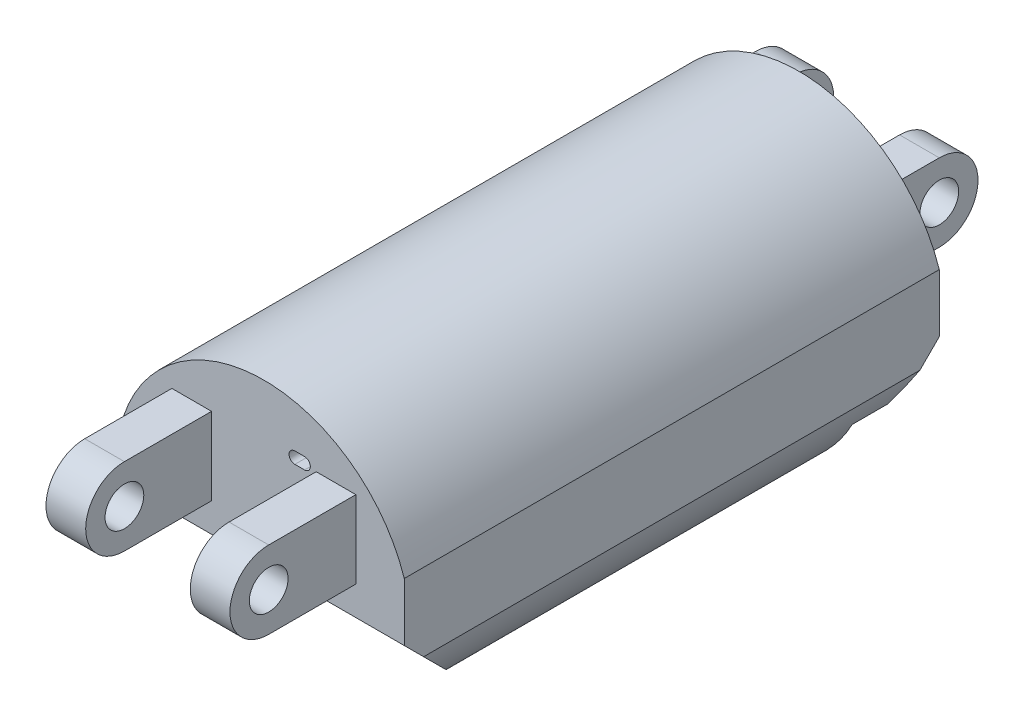
SolidWorks part; units mm, degrees
material "PET"
ref_plane "Front Plane" through (0, 0, 0) normal (0, 0, 1) x (1, 0, 0)
ref_plane "Top Plane" through (0, 0, 0) normal (0, 1, 0) x (1, 0, 0)
ref_plane "Right Plane" through (0, 0, 0) normal (1, 0, 0) x (0, 0, -1)
sketch "Sketch1" plane through (0, 0, 0) normal (0, 0, 1) x (1, 0, 0)
  line L0 (0, 0) -> (0, 5.08)
  line L3 (18.415, 5.08) -> (18.415, 0)
  arc A2 (0, 5.08) -> (18.415, 5.08) centre (9.2075, 2.0562) cw
  arc A3 (0, 0) -> (18.415, 0) centre (9.2075, 3.0238) ccw
  point P2 (9.2075, -6.6675)
  point P8 (9.2075, 11.7475)
  dimension "D1" = 18.415
  dimension "D2" = 18.415
  dimension "D3" = 5.08
extrude "Boss-Extrude1" add sketch "Sketch1" along normal mid plane 35.0838 contours A2 L3 A3 L0
sketch "Sketch2" plane through (0, 0, 0) normal (1, 0, 0) x (0, 0, -1)
  line L4 (15.875, 2.54) -> (-49984.125, 2.54) construction
  line L5 (17.5419, 5.08) -> (17.5419, 0) construction
  line L6 (-17.5419, 5.08) -> (-17.5419, 0) construction
  line L10 (0, -1000) -> (0, 49000) construction
  line L18 (-17.5419, 1.27) -> (-17.5419, -6.6675)
  line L23 (17.5419, -6.6675) -> (9.6044, -6.6675)
  line L24 (17.5419, 1.27) -> (17.5419, -6.6675)
  line L32 (-17.5419, -6.6675) -> (-9.6044, -6.6675)
  line L33 (-17.5419, -6.6675) -> (17.5419, -6.6675) construction
  line L34 (-9.6044, -6.6675) -> (-17.5419, 1.27)
  line L35 (9.6044, -6.6675) -> (17.5419, 1.27)
  line L36 (-17.5419, -6.6675) -> (17.5419, -6.6675) construction
  point P0 (-15.0884, 2.54)
  point P11 (17.5419, 2.54)
  point P14 (-17.5419, 2.54)
  dimension "D2" = 1.27
  dimension "D4" = 45
extrude "Cut-Extrude1" cut sketch "Sketch2" along normal through all
sketch "Sketch3" plane through (0, 0, 17.5419) normal (0, 0, 1) x (1, 0, 0)
  line L0 (21.7393, 2.54) -> (-3.7187, 2.54) construction
  line L2 (9.2075, 13.3103) -> (9.2075, -9.2077) construction
  arc A0 (18.415, 5.08) -> (0, 5.08) centre (9.2075, 2.0562) ccw construction
  arc A3 (18.415, 5.08) -> (0, 5.08) centre (9.2075, 2.0562) ccw
  arc A5 (17.2084, 4.6837) -> (1.2066, 4.6837) centre (9.2075, 2.0562) ccw
  arc A6 (6.0894, 9.879) -> (12.3256, 9.879) centre (9.2075, 10.4775) ccw
  arc A7 (17.2084, 0.3963) -> (1.2066, 0.3963) centre (9.2075, 3.0238) cw
  arc A8 (6.0894, -4.799) -> (12.3256, -4.799) centre (9.2075, -5.3975) cw
  point P9 (9.2075, 11.7475)
  point P14 (9.2075, 7.3025)
  dimension "D1" = 2.54
  dimension "D2" = 1.27
  dimension "D4" = 3.175
extrude "Cut-Extrude2" cut sketch "Sketch3" against normal through all both and the other way through all contours A8 A7
ref_plane "Plane1" through (14.605, 0, 0) normal (1, 0, 0) x (0, 0, -1)
sketch "Sketch4" plane through (14.605, 0, 0) normal (1, 0, 0) x (0, 0, -1)
  line L0 (-17.5419, 8.255) -> (-20.7169, 8.255)
  line L1 (-17.5419, 8.255) -> (-17.5419, 3.175)
  line L2 (-17.5419, 3.175) -> (-20.7169, 3.175)
  line L3 (-17.5419, 5.08) -> (-17.5419, 1.27) construction
  line L4 (-16.2719, 0) -> (16.2719, 0) construction
  arc A0 (-20.7169, 8.255) -> (-20.7169, 3.175) centre (-20.7169, 5.715) ccw
  circle A1 centre (-20.7169, 5.715) radius 1.27
  dimension "D2" = 2.54
  dimension "D1" = 5.08
  dimension "D3" = 3.175
  dimension "D4" = 3.175
extrude "Boss-Extrude2" add sketch "Sketch4" along normal mid plane 1.27
sketch "Sketch5" plane through (13.97, 0, 0) normal (-1, 0, 0) x (0, 0, 1)
  line L3 (17.5419, 8.255) -> (17.5419, 3.175)
  line L4 (17.5419, 3.175) -> (20.7169, 3.175)
  line L5 (20.7169, 8.255) -> (17.5419, 8.255)
  line L6 (17.5419, 8.255) -> (17.5419, 3.175)
  line L7 (17.5419, 3.175) -> (20.7169, 3.175)
  line L8 (20.7169, 8.255) -> (17.5419, 8.255)
  circle A0 centre (20.7169, 5.715) radius 1.27 construction
  arc A1 (20.7169, 3.175) -> (20.7169, 8.255) centre (20.7169, 5.715) ccw
  arc A2 (20.7169, 3.175) -> (20.7169, 8.255) centre (20.7169, 5.715) ccw
  circle A3 centre (20.7169, 5.715) radius 1.27
  dimension "D1" = 0
extrude "Boss-Extrude3" add sketch "Sketch5" along normal blind 1.3323
ref_plane "Plane2" through (9.2075, 0, 0) normal (1, 0, 0) x (0, 0, -1)
mirror "Mirror1" about plane through (9.2075, 0, 0) normal (1, 0, 0) of "Boss-Extrude3", "Boss-Extrude2"
mirror "Mirror2" about plane through (0, 0, 0) normal (0, 0, 1) of "Mirror1", "Boss-Extrude3", "Boss-Extrude2"
sketch "Sketch8" [suppressed] plane through (15.24, 0, 0) normal (1, 0, 0) x (0, 0, -1)
  line L3 (17.5419, 8.255) -> (17.5419, 3.175)
  line L4 (17.5419, 3.175) -> (20.7169, 3.175)
  line L5 (20.7169, 8.255) -> (17.5419, 8.255)
  line L6 (17.5419, 8.255) -> (17.5419, 3.175)
  line L7 (17.5419, 3.175) -> (20.7169, 3.175)
  line L8 (20.7169, 8.255) -> (17.5419, 8.255)
  circle A0 centre (20.7169, 5.715) radius 1.27 construction
  arc A1 (20.7169, 3.175) -> (20.7169, 8.255) centre (20.7169, 5.715) ccw
  arc A2 (20.7169, 3.175) -> (20.7169, 8.255) centre (20.7169, 5.715) ccw
  circle A3 centre (20.7169, 5.715) radius 1.27
  dimension "D1" = 0
extrude "Cut-Extrude4" [suppressed] cut sketch "Sketch8" against normal blind 1.27
sketch "Sketch9" [suppressed] plane through (12.6377, 0, 0) normal (-1, 0, 0) x (0, 0, 1)
  line L3 (-17.5419, 8.255) -> (-20.7169, 8.255)
  line L4 (-20.7169, 3.175) -> (-17.5419, 3.175)
  line L5 (-17.5419, 3.175) -> (-17.5419, 8.255)
  line L6 (-17.5419, 8.255) -> (-20.7169, 8.255)
  line L7 (-20.7169, 3.175) -> (-17.5419, 3.175)
  line L8 (-17.5419, 3.175) -> (-17.5419, 8.255)
  circle A1 centre (-20.7169, 5.715) radius 1.27
  circle A2 centre (-20.7169, 5.715) radius 1.27
  arc A3 (-20.7169, 8.255) -> (-20.7169, 3.175) centre (-20.7169, 5.715) ccw
  arc A4 (-20.7169, 8.255) -> (-20.7169, 3.175) centre (-20.7169, 5.715) ccw
  dimension "D1" = 0
  dimension "D2" = 0
extrude "Boss-Extrude5" [suppressed] add sketch "Sketch9" along normal blind 0.635
mirror "Mirror5" [suppressed] about plane through (9.2075, 0, 0) normal (1, 0, 0)
sketch "Sketch10" plane through (15.24, 0, 0) normal (1, 0, 0) x (0, 0, -1)
  line L0 (-20.7169, 3.175) -> (-17.5419, 3.175) construction
  line L1 (-17.5419, 8.255) -> (-23.2569, 8.255)
  line L2 (-17.5419, 8.255) -> (-17.5419, 3.175)
  line L3 (-17.5419, 3.175) -> (-23.2569, 3.175)
  arc A1 (-23.2569, 8.255) -> (-23.2569, 3.175) centre (-23.2569, 5.715) ccw
  circle A2 centre (-23.2569, 5.715) radius 1.27
  arc A3 (-20.7169, 8.255) -> (-20.7169, 3.175) centre (-20.7169, 5.715) ccw construction
  dimension "D1" = 2.54
extrude "Boss-Extrude6" add sketch "Sketch10" against normal up to surface (2.6023 mm away) up to face at (12.6377, 5.715, 19.7644)
sketch "Sketch12" plane through (3.175, 0, 0) normal (-1, 0, 0) x (0, 0, 1)
  line L0 (20.7169, 3.175) -> (17.5419, 3.175) construction
  line L1 (17.5419, 8.255) -> (23.2569, 8.255)
  line L2 (17.5419, 8.255) -> (17.5419, 3.175)
  line L3 (17.5419, 3.175) -> (23.2569, 3.175)
  arc A0 (23.2569, 8.255) -> (23.2569, 3.175) centre (23.2569, 5.715) cw
  arc A1 (23.2569, 3.175) -> (23.2569, 8.255) centre (23.2569, 5.715) ccw construction
extrude "Boss-Extrude7" add sketch "Sketch12" against normal up to surface (2.6023 mm away) up to face at (5.7773, 5.715, 21.9869)
sketch "Sketch11" plane through (15.24, 0, 0) normal (1, 0, 0) x (0, 0, -1)
  circle A0 centre (-23.2569, 5.715) radius 1.27
  arc A1 (-22.9394, 6.9447) -> (-22.9394, 4.4853) centre (-20.7169, 5.715) ccw construction
extrude "Cut-Extrude5" cut sketch "Sketch11" against normal up to surface (12.065 mm away) up to face at (3.175, 5.715, 21.0344)
sketch "Sketch16" [suppressed] plane through (12.6377, 0, 0) normal (-1, 0, 0) x (0, 0, 1)
  line L3 (23.2569, 8.255) -> (17.5419, 8.255)
  line L4 (17.5419, 8.255) -> (17.5419, 3.175)
  line L5 (17.5419, 3.175) -> (23.2569, 3.175)
  line L6 (23.2569, 8.255) -> (17.5419, 8.255)
  line L7 (17.5419, 8.255) -> (17.5419, 3.175)
  line L8 (17.5419, 3.175) -> (23.2569, 3.175)
  circle A0 centre (23.2569, 5.715) radius 1.27 construction
  arc A1 (23.2569, 3.175) -> (23.2569, 8.255) centre (23.2569, 5.715) ccw
  arc A2 (23.2569, 3.175) -> (23.2569, 8.255) centre (23.2569, 5.715) ccw
  circle A3 centre (23.2569, 5.715) radius 1.27
  dimension "D1" = 0
extrude "Cut-Extrude7" [suppressed] cut sketch "Sketch16" against normal blind 1.27
sketch "Sketch17" [suppressed] plane through (15.24, 0, 0) normal (1, 0, 0) x (0, 0, -1)
  line L3 (-17.5419, 8.255) -> (-23.2569, 8.255)
  line L4 (-23.2569, 3.175) -> (-17.5419, 3.175)
  line L5 (-17.5419, 3.175) -> (-17.5419, 8.255)
  line L6 (-17.5419, 8.255) -> (-23.2569, 8.255)
  line L7 (-23.2569, 3.175) -> (-17.5419, 3.175)
  line L8 (-17.5419, 3.175) -> (-17.5419, 8.255)
  circle A0 centre (-23.2569, 5.715) radius 1.27 construction
  arc A1 (-23.2569, 8.255) -> (-23.2569, 3.175) centre (-23.2569, 5.715) ccw
  arc A2 (-23.2569, 8.255) -> (-23.2569, 3.175) centre (-23.2569, 5.715) ccw
  circle A3 centre (-23.2569, 5.715) radius 1.27
  dimension "D1" = 0
extrude "Boss-Extrude10" [suppressed] add sketch "Sketch17" against normal blind 2.54
sketch "Sketch19" [suppressed] plane through (13.97, 0, 0) normal (1, 0, 0) x (0, 0, -1)
  line L3 (20.7169, 8.255) -> (17.5419, 8.255)
  line L4 (17.5419, 8.255) -> (17.5419, 3.175)
  line L5 (17.5419, 3.175) -> (20.7169, 3.175)
  line L6 (20.7169, 8.255) -> (17.5419, 8.255)
  line L7 (17.5419, 8.255) -> (17.5419, 3.175)
  line L8 (17.5419, 3.175) -> (20.7169, 3.175)
  circle A0 centre (20.7169, 5.715) radius 1.27 construction
  arc A1 (20.7169, 3.175) -> (20.7169, 8.255) centre (20.7169, 5.715) ccw
  arc A2 (20.7169, 3.175) -> (20.7169, 8.255) centre (20.7169, 5.715) ccw
  circle A3 centre (20.7169, 5.715) radius 1.27
  dimension "D1" = 0
extrude "Boss-Extrude11" [suppressed] add sketch "Sketch19" along normal blind 1.143
mirror "Mirror6" [suppressed] about plane through (9.2075, 0, 0) normal (1, 0, 0)
sketch "Sketch20" plane through (0, 0, -17.5419) normal (0, 0, -1) x (-1, 0, 0)
  line L0 (-21.8226, 5.715) -> (5.8887, 5.715) construction
  line L1 (-18.415, 1.27) -> (-18.415, 0) construction
  line L2 (-17.78, 5.715) -> (-15.24, 5.715)
  line L3 (-17.78, 5.715) -> (-17.78, -6.985)
  line L4 (-17.78, -6.985) -> (-15.24, -6.985)
  line L5 (-15.24, 5.715) -> (-15.24, -6.985)
  line L6 (-3.175, 5.715) -> (-0.635, 5.715)
  line L7 (-3.175, 5.715) -> (-3.175, -6.985)
  line L8 (-3.175, -6.985) -> (-0.635, -6.985)
  line L9 (-0.635, 5.715) -> (-0.635, -6.985)
  dimension "D1" = 2.54
  dimension "D2" = 2.54
  dimension "D3" = 0.635
  dimension "D4" = 0.635
  dimension "D5" = 12.7
  dimension "D6" = 12.7
  dimension "D7" = 5.715
extrude "Cut-Extrude9" cut sketch "Sketch20" against normal blind 5.08
sketch "Sketch21" plane through (0, 0, -17.5419) normal (0, 0, -1) x (-1, 0, 0)
  line L0 (-7.1755, 8.1788) -> (-6.5405, 8.1788) construction
  line L1 (-6.5405, 2.8702) -> (-11.8745, 2.8702)
  line L2 (-6.5405, 2.8702) -> (-6.5405, 8.5598)
  line L3 (-6.5405, 8.5598) -> (-11.8745, 8.5598)
  line L4 (-11.8745, 2.8702) -> (-11.8745, 8.5598)
  line L5 (-6.5405, 2.8702) -> (-11.8745, 8.5598) construction
  line L6 (-6.5405, 8.5598) -> (-11.8745, 2.8702) construction
  line L7 (-7.1755, 8.5598) -> (-6.5405, 8.5598)
  line L8 (-7.1755, 7.7978) -> (-6.5405, 7.7978)
  arc A0 (-7.1755, 8.5598) -> (-7.1755, 7.7978) centre (-7.1755, 8.1788) ccw
  arc A1 (-6.5405, 7.7978) -> (-6.5405, 8.5598) centre (-6.5405, 8.1788) ccw
  point P0 (-9.2075, 5.715)
  point P5 (-6.858, 8.1788)
  dimension "D6" = 6.5405
  dimension "D1" = 5.334
  dimension "D2" = 5.6896
  dimension "D3" = 5.715
  dimension "D4" = 0.635
  dimension "D5" = 0.762
extrude "Cut-Extrude10" cut sketch "Sketch21" against normal blind 15.875 and the other way blind 10.16
fillet "Fillet1" radius 0.635 2 edges at (1.905, 5.715, -17.5419) (16.51, 5.715, -17.5419)
sketch "Sketch22" plane through (0, 0, 0) normal (-1, 0, 0) x (0, 0, 1)
  text T0 "Pointer 3"
extrude "Cut-Extrude11" cut sketch "Sketch22" against normal blind 1
sketch "Sketch24" plane through (0, 0, 17.5419) normal (0, 0, 1) x (1, 0, 0)
  line L0 (18.415, 1.27) -> (0, 1.27) construction
  line L1 (6.5405, 8.7376) -> (11.8745, 8.7376)
  line L2 (6.5405, 8.7376) -> (6.5405, 3.048)
  line L3 (6.5405, 3.048) -> (11.8745, 3.048)
  line L4 (11.8745, 8.7376) -> (11.8745, 3.048)
  line L5 (6.5405, 8.7376) -> (11.8745, 3.048) construction
  line L6 (6.5405, 3.048) -> (11.8745, 8.7376) construction
  line L7 (18.415, 1.27) -> (0, 1.27)
  line L8 (11.8745, 8.3566) -> (11.2395, 8.3566) construction
  line L9 (11.8745, 7.9756) -> (11.2395, 7.9756)
  line L10 (11.8745, 8.7376) -> (11.2395, 8.7376)
  arc A1 (11.8745, 7.9756) -> (11.8745, 8.7376) centre (11.8745, 8.3566) ccw
  arc A2 (11.2395, 8.7376) -> (11.2395, 7.9756) centre (11.2395, 8.3566) ccw
  point P0 (9.2075, 5.8928)
  point P7 (9.2075, 1.27)
  point P8 (9.2075, 3.048)
  point P11 (11.557, 8.3566)
  dimension "D3" = 3.048
  dimension "D1" = 5.6896
  dimension "D2" = 5.334
  dimension "D4" = 0.762
  dimension "D5" = 0.635
extrude "Cut-Extrude12" cut sketch "Sketch24" against normal blind 17.78 contours L1 A2 L9 L4 | L4 A1
equation "\"D1@Sketch1\"  = 0.725"
equation "\"D1@Boss-Extrude1\"=2.125*.65"
